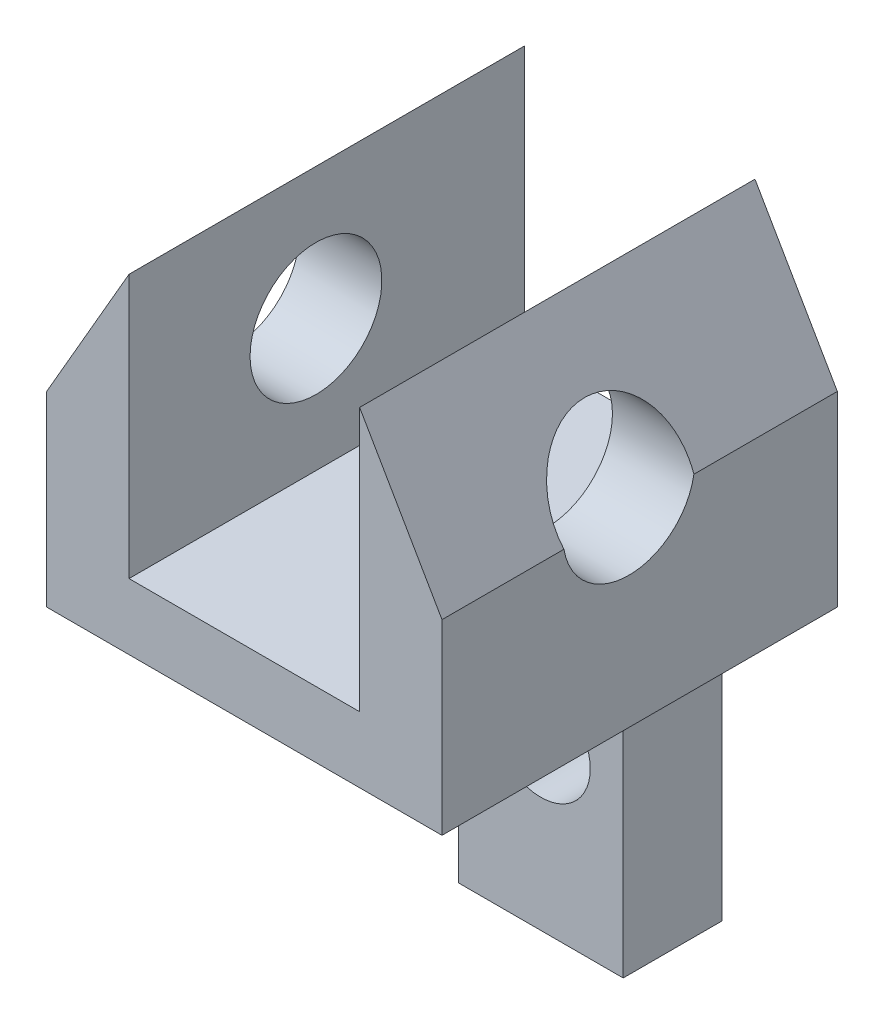
SolidWorks part; units mm, degrees
ref_plane "Front Plane" through (0, 0, 0) normal (0, 0, 1) x (1, 0, 0)
ref_plane "Top Plane" through (0, 0, 0) normal (0, 1, 0) x (1, 0, 0)
ref_plane "Right Plane" through (0, 0, 0) normal (1, 0, 0) x (0, 0, -1)
sketch "Sketch1" plane through (0, 0, 0) normal (0, 1, 0) x (1, 0, 0)
  line L1 (-6, -6) -> (6, -6)
  line L2 (-6, -6) -> (-6, 6)
  line L3 (-6, 6) -> (6, 6)
  line L4 (6, -6) -> (6, 6)
  line L5 (-6, -6) -> (6, 6) construction
  line L6 (-6, 6) -> (6, -6) construction
  point P0 (0, 0)
  dimension "D1" = 12
  dimension "D2" = 12
extrude "Boss-Extrude1" add sketch "Sketch1" along normal blind 2
sketch "Sketch2" plane through (0, 2, 0) normal (0, 1, 0) x (1, 0, 0)
  line L0 (-6, -6) -> (6, -6) construction
  line L1 (-6, 6) -> (-3.5, 6)
  line L2 (-6, 6) -> (-6, -6)
  line L3 (-6, -6) -> (-3.5, -6)
  line L4 (-3.5, 6) -> (-3.5, -6)
  line L5 (6, 6) -> (-6, 6) construction
  line L6 (6, -6) -> (3.5, -6)
  line L7 (6, -6) -> (6, 6)
  line L8 (6, 6) -> (3.5, 6)
  line L9 (3.5, -6) -> (3.5, 6)
  line L10 (-3.5, 6) -> (3.5, 6) construction
  line L11 (-6, 6) -> (6, 6) construction
  point P16 (0, 6)
  point P17 (0, 6)
  dimension "D1" = 7
extrude "Boss-Extrude2" add sketch "Sketch2" along normal blind 8
sketch "Sketch4" plane through (3.5, 0, 0) normal (-1, 0, 0) x (0, 0, 1)
  line L0 (-6, 2) -> (6, 2) construction
  circle A0 centre (0.3261, 6) radius 2
  dimension "D1" = 4
  dimension "D2" = 4
sketch "Sketch5" plane through (0, 0, 6) normal (0, 0, 1) x (1, 0, 0)
  line L0 (-3.5, 10) -> (-6, 5.6699)
  line L1 (-3.5, 10) -> (-3.5, 2) construction
  line L2 (-6, 10) -> (-6, 0) construction
  line L3 (0, 0) -> (0, 10.4395) construction
  line L4 (3.5, 10) -> (6, 5.6699)
  line L5 (3.5, 10) -> (3.5, 2) construction
  line L6 (6, 10) -> (6, 0) construction
  line L7 (3.5, 10) -> (6, 10)
  line L8 (6, 10) -> (6, 5.6699)
  line L9 (-6, 10) -> (-6, 5.6699)
  line L10 (-3.5, 10) -> (-6, 10)
  dimension "D1" = 30
  dimension "D2" = 30
extrude "Cut-Extrude1" cut sketch "Sketch5" against normal through all
extrude "Cut-Extrude2" cut sketch "Sketch4" against normal through all and the other way through all
sketch "Sketch6" plane through (0, 0, 0) normal (0, -1, 0) x (1, 0, 0)
  line L0 (6, -6) -> (-6, -6) construction
  line L1 (2.5, -6) -> (-2.5, -6)
  line L2 (2.5, -6) -> (2.5, -3)
  line L3 (2.5, -3) -> (-2.5, -3)
  line L4 (-2.5, -6) -> (-2.5, -3)
  point P6 (0, -6)
  dimension "D1" = 5
  dimension "D2" = 3
extrude "Boss-Extrude3" add sketch "Sketch6" along normal blind 10
ref_point "Point1"
hole_wizard "Ø3.0mm Dowel Hole1" positions "Sketch7" profile "Sketch8" hole size "Ø3.0" standard "ANSI Metric"
sketch "Sketch7" plane through (0, 0, -3) normal (0, 0, 1) x (1, 0, 0)
  point P0 (0, -5)
sketch "Sketch8" plane through (0, -5, -3) normal (1, 0, 0) x (0, -1, 0)
  line L0 (0, 0) -> (0, 3.9013)
  line L1 (0, 3.9013) -> (1.5, 3)
  line L2 (1.5, 3) -> (1.5, 0)
  line L5 (1.5, 0) -> (0, 0)
  line L10 (0, 3.9013) -> (-1.5, 3) construction
  line L11 (0, -6.35) -> (0, 107.95) construction
  dimension "Hole Dia." = 3
  dimension "Hole Depth" = 3
  dimension "Drill Angle" = 118
